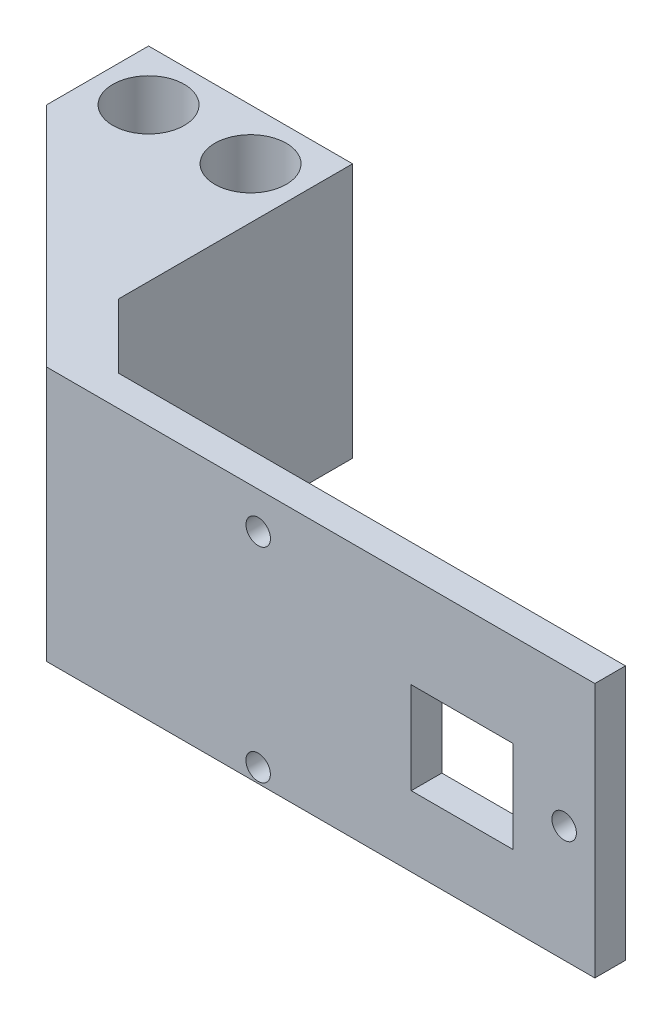
SolidWorks part; units mm, degrees
ref_plane "Front Plane" through (0, 0, 0) normal (0, 0, 1) x (1, 0, 0)
ref_plane "Top Plane" through (0, 0, 0) normal (0, 1, 0) x (1, 0, 0)
ref_plane "Right Plane" through (0, 0, 0) normal (1, 0, 0) x (0, 0, -1)
sketch "Sketch1" plane through (0, 0, 0) normal (0, 1, 0) x (1, 0, 0)
  line L0 (0, 0) -> (0, -3)
  line L1 (0, -3) -> (-53.75, -3)
  line L2 (-53.75, -3) -> (-76, 19.25)
  line L3 (-76, 19.25) -> (-76, 29.25)
  line L4 (-76, 29.25) -> (-56, 29.25)
  line L5 (-56, 29.25) -> (-56, 6.3211)
  line L6 (-56, 6.3211) -> (-49.6789, 0)
  line L7 (-49.6789, 0) -> (0, 0)
  line L8 (-53, 11.4) -> (-53, 4.1) construction
  line L9 (-193.1, 19.25) -> (6.9, 19.25) construction
  dimension "D1" = 3
  dimension "D2" = 20
  dimension "D3" = 3
  dimension "D4" = 10
  dimension "D5" = 5
  dimension "D7" = 45
extrude "Boss-Extrude1" add sketch "Sketch1" along normal blind 25
sketch "Sketch2" plane through (0, 0, 3) normal (0, 0, 1) x (1, 0, 0)
  line L1 (-8, 6.9) -> (-18, 6.9)
  line L2 (-8, 6.9) -> (-8, 15.9)
  line L3 (-8, 15.9) -> (-18, 15.9)
  line L4 (-18, 6.9) -> (-18, 15.9)
  line L5 (-8, 6.9) -> (-18, 15.9) construction
  line L6 (-8, 15.9) -> (-18, 6.9) construction
  point P0 (-13, 11.4)
  dimension "D1" = 10
  dimension "D2" = 9
extrude "Cut-Extrude1" cut sketch "Sketch2" against normal through all
hole_wizard "CBORE for M3 Pan Head Screw1" positions "Sketch3" profile "Sketch4" counterbore size "M3" standard "ISO" end condition through all
sketch "Sketch3" plane through (0, 25, 0) normal (0, 1, 0) x (1, 0, 0)
  line L0 (-71, 24.25) -> (-61, 24.25) construction
  line L2 (-76, 29.25) -> (-76, 19.25) construction
  line L3 (-56, 29.25) -> (-76, 29.25) construction
  point P0 (-71, 24.25)
  point P2 (-61, 24.25)
  dimension "D1" = 10
  dimension "D2" = 5
  dimension "D3" = 5
sketch "Sketch4" plane through (-71, 25, -24.25) normal (1, 0, 0) x (0, 0, 1)
  line L0 (0, 0) -> (0, 25)
  line L1 (0, 25) -> (1.7, 25)
  line L3 (1.7, 25) -> (1.7, 5)
  line L4 (1.7, 5) -> (3.5, 5)
  line L5 (3.5, 5) -> (3.5, 0)
  line L7 (3.5, 0) -> (0, 0)
  line L11 (0, -6.35) -> (0, 107.95) construction
  dimension "Thru Hole Dia." = 3.4
  dimension "Thru Hole Depth" = 25
  dimension "C'Bore Dia." = 7
  dimension "C'Bore Depth" = 5
hole_wizard "CBORE for M2 Hex Socket Head Cap Screw1" positions "Sketch5" profile "Sketch6" counterbore size "M2" standard "ISO" end condition through all
sketch "Sketch5" plane through (0, 0, 0) normal (0, 0, 1) x (1, 0, 0)
  point P0 (-33, 21.4)
  point P3 (-33.008, 1.392)
  point P6 (-3.01, 11.4)
sketch "Sketch6" plane through (-33, 21.4, 0) normal (1, 0, 0) x (0, 1, 0)
  line L0 (0, 0) -> (0, 3)
  line L1 (0, 3) -> (1.2, 3)
  line L3 (1.2, 3) -> (1.2, 1)
  line L4 (2.2, 1) -> (1.2, 1)
  line L5 (2.2, 1) -> (2.2, 0.025)
  line L6 (2.2, 0.025) -> (2.225, 0)
  line L7 (2.225, 0) -> (0, 0)
  line L8 (-2.2, 0.025) -> (-2.225, 0) construction
  line L11 (0, -6.35) -> (0, 107.95) construction
  dimension "Thru Hole Dia." = 2.4
  dimension "Thru Hole Depth" = 3
  dimension "C'Bore Dia." = 4.4
  dimension "C'Bore Depth" = 1
  dimension "Near C'Sink Dia." = 4.45
  dimension "Near C'Sink Angle" = 90
